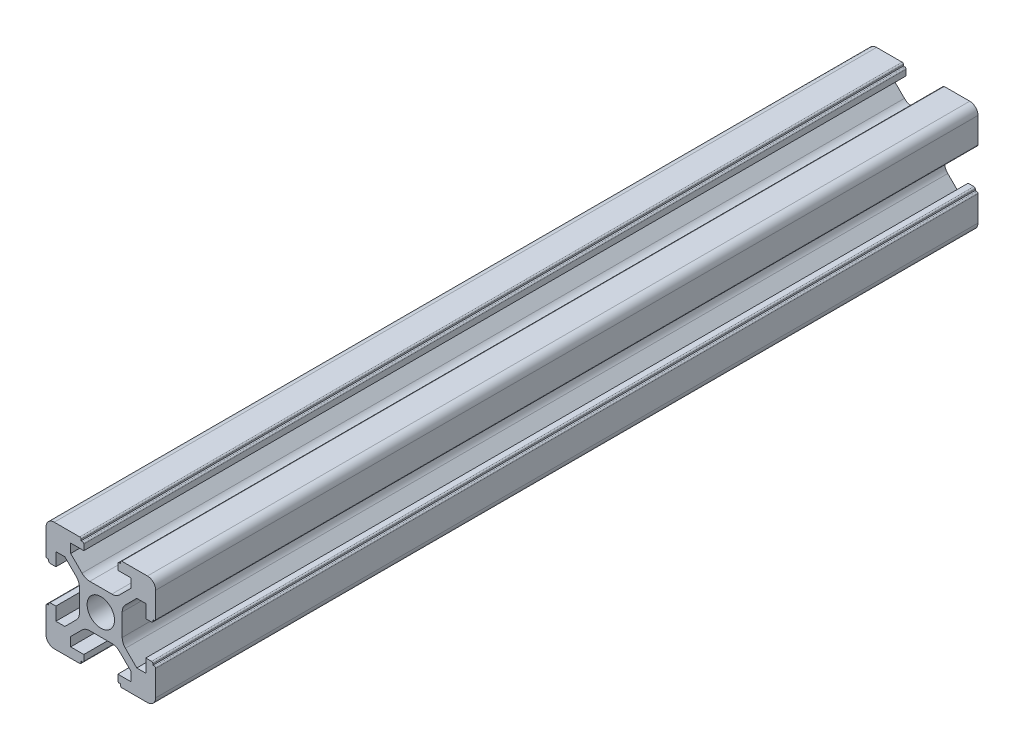
SolidWorks part; units mm, degrees
ref_plane "Front Plane" through (0, 0, 0) normal (0, 0, 1) x (1, 0, 0)
ref_plane "Top Plane" through (0, 0, 0) normal (0, 1, 0) x (1, 0, 0)
ref_plane "Right Plane" through (0, 0, 0) normal (1, 0, 0) x (0, 0, -1)
sketch "Sketch1" plane through (0, 0, 0) normal (0, 0, 1) x (1, 0, 0)
  line L0 (0, 0) -> (-10, 10) construction
  line L5 (0, 0) -> (10, 10) construction
  line L6 (22.7721, 0) -> (-22.7721, 0) construction
  line L7 (-8.5, 10) -> (-3.85, 10)
  line L8 (8.5, 10) -> (3.85, 10)
  line L9 (-3.6, 9.75) -> (-3.6, 9.5)
  line L10 (-3.6, 9.5) -> (-3.35, 9.5)
  line L11 (3.6, 9.75) -> (3.6, 9.5)
  line L12 (3.6, 9.5) -> (3.35, 9.5)
  line L13 (-3.1, 9.25) -> (-3.1, 8.2)
  line L14 (3.1, 9.25) -> (3.1, 8.2)
  line L15 (-3.1, 8.2) -> (-5.5, 8.2)
  line L16 (3.1, 8.2) -> (5.5, 8.2)
  line L17 (-3.4251, 4.4858) -> (-5.5, 6.5607)
  line L18 (-2.0109, 3.9) -> (2.0109, 3.9)
  line L19 (-5.5, 6.5607) -> (-5.5, 8.2)
  line L20 (5.5, 6.5607) -> (3.4251, 4.4858)
  line L21 (5.5, 6.5607) -> (5.5, 8.2)
  line L22 (10, 8.5) -> (10, 3.85)
  line L23 (10, -8.5) -> (10, -3.85)
  line L24 (9.75, 3.6) -> (9.5, 3.6)
  line L25 (9.5, 3.6) -> (9.5, 3.35)
  line L26 (9.75, -3.6) -> (9.5, -3.6)
  line L27 (9.5, -3.6) -> (9.5, -3.35)
  line L28 (9.25, 3.1) -> (8.2, 3.1)
  line L29 (9.25, -3.1) -> (8.2, -3.1)
  line L30 (8.2, 3.1) -> (8.2, 5.5)
  line L31 (8.2, -3.1) -> (8.2, -5.5)
  line L32 (4.4858, 3.4251) -> (6.5607, 5.5)
  line L33 (3.9, 2.0109) -> (3.9, -2.0109)
  line L34 (6.5607, 5.5) -> (8.2, 5.5)
  line L35 (6.5607, -5.5) -> (4.4858, -3.4251)
  line L36 (6.5607, -5.5) -> (8.2, -5.5)
  line L37 (8.5, -10) -> (3.85, -10)
  line L38 (-8.5, -10) -> (-3.85, -10)
  line L39 (3.6, -9.75) -> (3.6, -9.5)
  line L40 (3.6, -9.5) -> (3.35, -9.5)
  line L41 (-3.6, -9.75) -> (-3.6, -9.5)
  line L42 (-3.6, -9.5) -> (-3.35, -9.5)
  line L43 (3.1, -9.25) -> (3.1, -8.2)
  line L44 (-3.1, -9.25) -> (-3.1, -8.2)
  line L45 (3.1, -8.2) -> (5.5, -8.2)
  line L46 (-3.1, -8.2) -> (-5.5, -8.2)
  line L47 (3.4251, -4.4858) -> (5.5, -6.5607)
  line L48 (2.0109, -3.9) -> (-2.0109, -3.9)
  line L49 (5.5, -6.5607) -> (5.5, -8.2)
  line L50 (-5.5, -6.5607) -> (-3.4251, -4.4858)
  line L51 (-5.5, -6.5607) -> (-5.5, -8.2)
  line L52 (-10, -8.5) -> (-10, -3.85)
  line L53 (-10, 8.5) -> (-10, 3.85)
  line L54 (-9.75, -3.6) -> (-9.5, -3.6)
  line L55 (-9.5, -3.6) -> (-9.5, -3.35)
  line L56 (-9.75, 3.6) -> (-9.5, 3.6)
  line L57 (-9.5, 3.6) -> (-9.5, 3.35)
  line L58 (-9.25, -3.1) -> (-8.2, -3.1)
  line L59 (-9.25, 3.1) -> (-8.2, 3.1)
  line L60 (-8.2, -3.1) -> (-8.2, -5.5)
  line L61 (-8.2, 3.1) -> (-8.2, 5.5)
  line L62 (-4.4858, -3.4251) -> (-6.5607, -5.5)
  line L63 (-3.9, -2.0109) -> (-3.9, 2.0109)
  line L64 (-6.5607, -5.5) -> (-8.2, -5.5)
  line L65 (-6.5607, 5.5) -> (-4.4858, 3.4251)
  line L66 (-6.5607, 5.5) -> (-8.2, 5.5)
  circle A5 centre (0, 0) radius 2.5
  arc A6 (-8.5, -10) -> (-10, -8.5) centre (-8.5, -8.5) cw
  arc A7 (10, -8.5) -> (8.5, -10) centre (8.5, -8.5) cw
  arc A8 (8.5, 10) -> (10, 8.5) centre (8.5, 8.5) cw
  arc A9 (-8.5, 10) -> (-10, 8.5) centre (-8.5, 8.5) ccw
  arc A10 (-4.4858, -3.4251) -> (-3.9, -2.0109) centre (-5.9, -2.0109) ccw
  arc A11 (-2.0109, -3.9) -> (-3.4251, -4.4858) centre (-2.0109, -5.9) ccw
  arc A12 (3.4251, -4.4858) -> (2.0109, -3.9) centre (2.0109, -5.9) ccw
  arc A13 (3.9, -2.0109) -> (4.4858, -3.4251) centre (5.9, -2.0109) ccw
  arc A14 (4.4858, 3.4251) -> (3.9, 2.0109) centre (5.9, 2.0109) ccw
  arc A15 (3.4251, 4.4858) -> (2.0109, 3.9) centre (2.0109, 5.9) cw
  arc A16 (-3.4251, 4.4858) -> (-2.0109, 3.9) centre (-2.0109, 5.9) ccw
  arc A17 (-3.9, 2.0109) -> (-4.4858, 3.4251) centre (-5.9, 2.0109) ccw
  arc A18 (10, 3.85) -> (9.75, 3.6) centre (9.75, 3.85) cw
  arc A19 (9.5, 3.35) -> (9.25, 3.1) centre (9.25, 3.35) cw
  arc A20 (10, -3.85) -> (9.75, -3.6) centre (9.75, -3.85) ccw
  arc A21 (9.5, -3.35) -> (9.25, -3.1) centre (9.25, -3.35) ccw
  arc A22 (3.85, -10) -> (3.6, -9.75) centre (3.85, -9.75) cw
  arc A23 (3.1, -9.25) -> (3.35, -9.5) centre (3.35, -9.25) ccw
  arc A24 (-3.1, -9.25) -> (-3.35, -9.5) centre (-3.35, -9.25) cw
  arc A25 (-3.85, -10) -> (-3.6, -9.75) centre (-3.85, -9.75) ccw
  arc A26 (-10, -3.85) -> (-9.75, -3.6) centre (-9.75, -3.85) cw
  arc A27 (-9.25, -3.1) -> (-9.5, -3.35) centre (-9.25, -3.35) ccw
  arc A28 (-9.5, 3.35) -> (-9.25, 3.1) centre (-9.25, 3.35) ccw
  arc A29 (-10, 3.85) -> (-9.75, 3.6) centre (-9.75, 3.85) ccw
  arc A30 (-3.1, 9.25) -> (-3.35, 9.5) centre (-3.35, 9.25) ccw
  arc A31 (-3.85, 10) -> (-3.6, 9.75) centre (-3.85, 9.75) cw
  arc A32 (3.35, 9.5) -> (3.1, 9.25) centre (3.35, 9.25) ccw
  arc A33 (3.85, 10) -> (3.6, 9.75) centre (3.85, 9.75) ccw
  point P6 (-3.1, 9.5)
  point P7 (0, 0)
  point P28 (9.5, 3.1)
  point P46 (3.1, -9.5)
  point P63 (-9.5, -3.1)
  point P77 (0, 0)
  point P123 (-3.1, 9.5)
  point P126 (-3.6, 10)
  point P129 (3.1, 9.5)
  point P132 (3.6, 10)
  dimension "D1" = 45
  dimension "D4" = 7.2
  dimension "D2" = 5
  dimension "D13" = 1.5
  dimension "D14" = 2
  dimension "D15" = 0.25
  dimension "D3" = 20
  dimension "D5" = 0.5
  dimension "D6" = 6.2
  dimension "D7" = 1.8
  dimension "D8" = 11
  dimension "D9" = 0.75
  dimension "D10" = 6.1
  dimension "D11" = 0.75
  dimension "D12" = 4
extrude "Boss-Extrude1" add sketch "Sketch1" along normal blind 150
